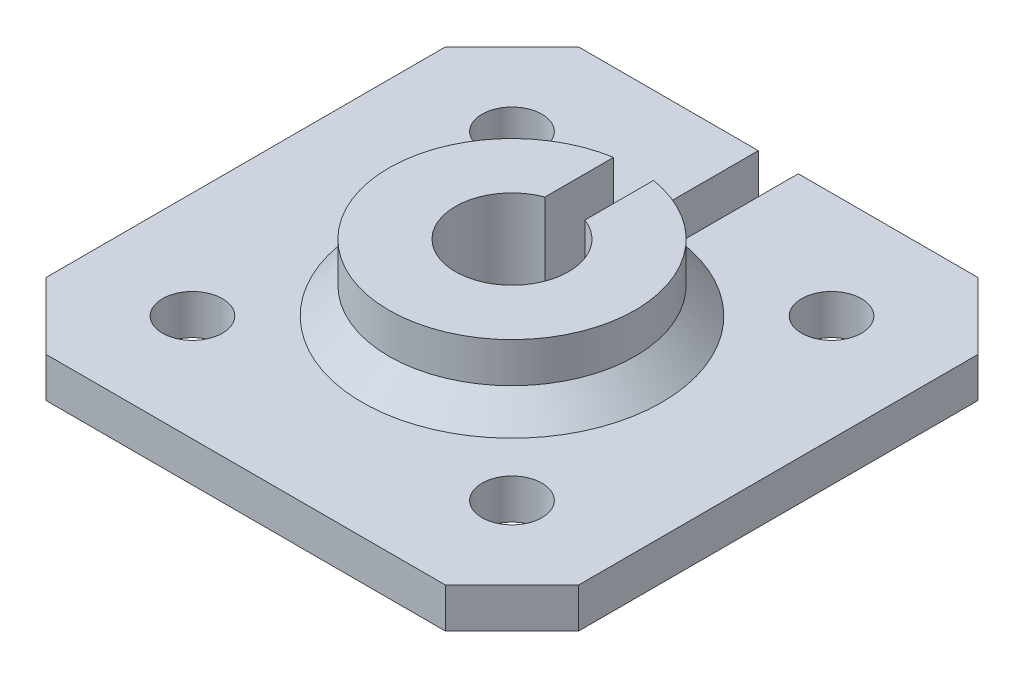
SolidWorks part; units mm, degrees
ref_plane "Front Plane" through (0, 0, 0) normal (0, 0, 1) x (1, 0, 0)
ref_plane "Top Plane" through (0, 0, 0) normal (0, 1, 0) x (1, 0, 0)
ref_plane "Right Plane" through (0, 0, 0) normal (1, 0, 0) x (0, 0, -1)
sketch "Sketch1" plane through (0, 0, 0) normal (0, 1, 0) x (1, 0, 0)
  line L1 (-20, 20) -> (20, 20)
  line L2 (-20, 20) -> (-20, -20)
  line L3 (-20, -20) -> (20, -20)
  line L4 (20, 20) -> (20, -20)
  line L5 (-20, 20) -> (20, -20) construction
  line L6 (-20, -20) -> (20, 20) construction
  circle A0 centre (0, 0) radius 4.25
  circle A1 centre (-12, -12) radius 2.25
  circle A2 centre (-12, 12) radius 2.25
  circle A3 centre (12, 12) radius 2.25
  circle A4 centre (12, -12) radius 2.25
  point P0 (0, 0)
  dimension "D3" = 8.5
  dimension "D5" = 4.5
  dimension "D1" = 40
  dimension "D2" = 40
  dimension "D4" = 12
  dimension "D6" = 12
  dimension "D7" = 12
  dimension "D8" = 12
extrude "Boss-Extrude1" add sketch "Sketch1" along normal blind 3
sketch "Sketch3" plane through (0, 3, 0) normal (0, 1, 0) x (1, 0, 0)
  circle A0 centre (0, 0) radius 4.25
  circle A1 centre (0, 0) radius 9.25
  dimension "D1" = 5
extrude "Boss-Extrude2" add sketch "Sketch3" along normal blind 5
sketch "Sketch2" plane through (0, 3, 0) normal (0, 1, 0) x (1, 0, 0)
  line L0 (0, 0) -> (0, 20)
  line L1 (20, 20) -> (-20, 20) construction
extrude "Cut-Extrude-Thin1" cut sketch "Sketch2" against normal blind 3 and the other way through all thin thin type mid plane wall 3
chamfer "Chamfer1" distance 5 angle 45 4 edges at (20, 1.5, -20) (20, 1.5, 20) (-20, 1.5, -20) (-20, 1.5, 20)
chamfer "Chamfer2" distance 2 angle 45 1 edges at (0, 3, 9.25)
